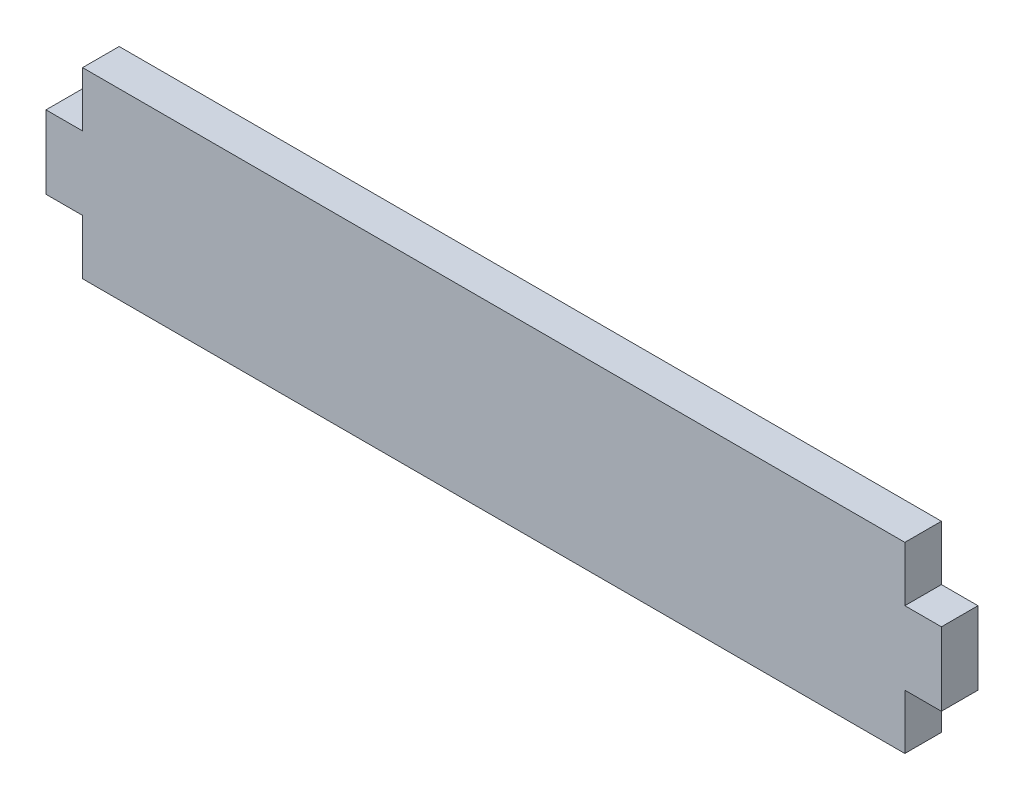
SolidWorks part; units mm, degrees
other "마크업1"
sketch "스케치2" plane through (-61.2, -12.5, 5) normal (0, 0, 1) x (1, 0, 0)
material "아크릴(내충격성)"
ref_plane "정면" through (0, 0, 0) normal (0, 0, 1) x (1, 0, 0)
ref_plane "윗면" through (0, 0, 0) normal (0, 1, 0) x (1, 0, 0)
ref_plane "우측면" through (0, 0, 0) normal (1, 0, 0) x (0, 0, -1)
sketch "스케치1" plane through (0, 0, 0) normal (0, 0, 1) x (1, 0, 0)
  line L0 (-61.2, -5) -> (-56.2, -5)
  line L1 (-56.2, 12.5) -> (56.2, 12.5)
  line L2 (-56.2, 12.5) -> (-56.2, 5)
  line L3 (-56.2, -12.5) -> (56.2, -12.5)
  line L4 (56.2, 12.5) -> (56.2, 5)
  line L5 (-56.2, 12.5) -> (56.2, -12.5) construction
  line L6 (-56.2, -12.5) -> (56.2, 12.5) construction
  line L7 (-61.2, 5) -> (-61.2, -5)
  line L8 (-61.2, 5) -> (-56.2, 5)
  line L9 (-56.2, -5) -> (-56.2, -12.5)
  line L10 (61.2, -5) -> (56.2, -5)
  line L11 (61.2, 5) -> (61.2, -5)
  line L12 (61.2, 5) -> (56.2, 5)
  line L13 (56.2, -5) -> (56.2, -12.5)
  point P0 (0, 0)
  dimension "D1" = 112.4
  dimension "D2" = 25
  dimension "D4" = 10
extrude "보스-돌출1" add sketch "스케치1" along normal blind 5
